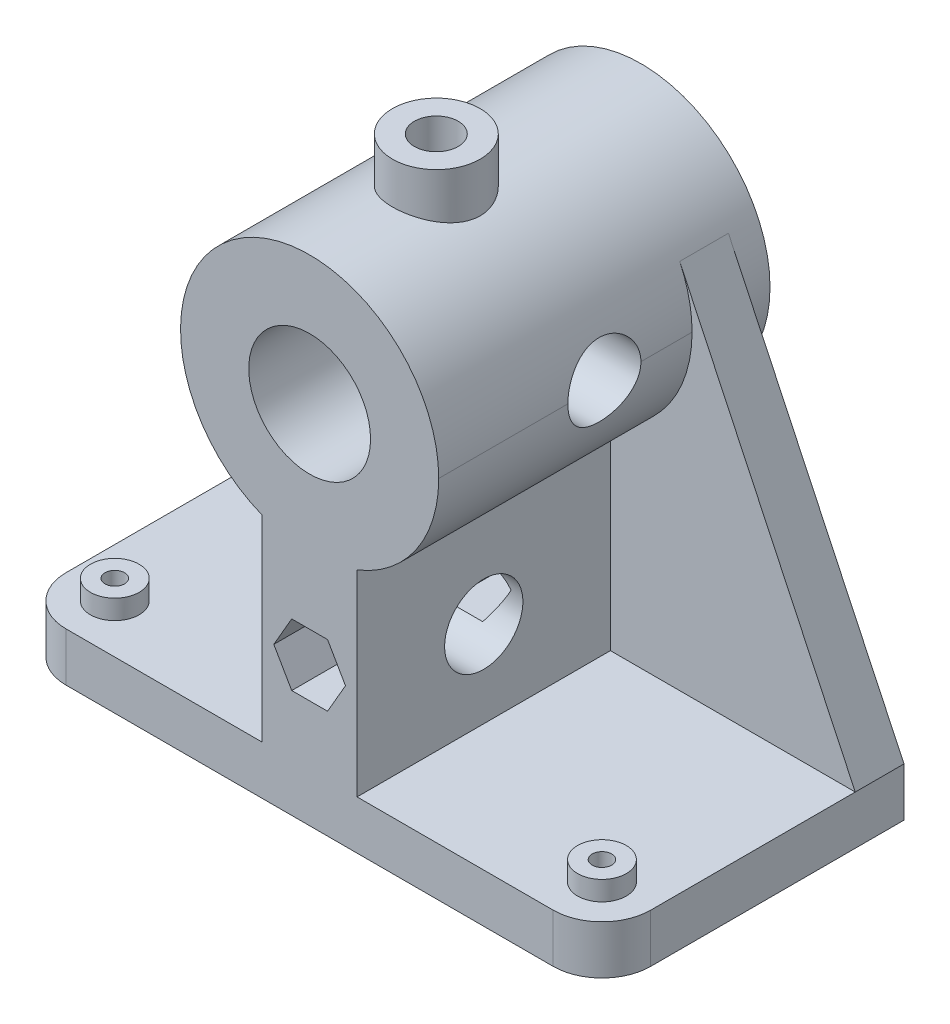
SolidWorks part; units mm, degrees
ref_plane "前视基准面" through (0, 0, 0) normal (0, 0, 1) x (1, 0, 0)
ref_plane "上视基准面" through (0, 0, 0) normal (0, 1, 0) x (1, 0, 0)
ref_plane "右视基准面" through (0, 0, 0) normal (1, 0, 0) x (0, 0, -1)
other "Configuration Table"
sketch "草图1" plane through (0, 0, 0) normal (0, 1, 0) x (1, 0, 0)
  line L1 (-60, 26) -> (60, 26)
  line L2 (-60, 26) -> (-60, -16)
  line L3 (-50, -26) -> (50, -26)
  line L4 (60, 26) -> (60, -16)
  line L5 (-60, 26) -> (60, -26) construction
  line L6 (-60, -26) -> (60, 26) construction
  arc A0 (60, -16) -> (50, -26) centre (50, -16) cw
  arc A1 (-50, -26) -> (-60, -16) centre (-50, -16) cw
  point P0 (0, 0)
  dimension "D1" = 10
  dimension "D3" = 52
  dimension "D2" = 120
extrude "凸台-拉伸1" add sketch "草图1" along normal blind 10
sketch "草图2" plane through (0, 0, 0) normal (0, 0, 1) x (1, 0, 0)
  circle A0 centre (0, 75) radius 26.5
  dimension "D2" = 53
  dimension "D1" = 75
extrude "凸台-拉伸2" add sketch "草图2" along normal blind 26 and the other way blind 42 separate body
sketch "草图3" plane through (0, 0, 26) normal (0, 0, 1) x (1, 0, 0)
  circle A0 centre (0, 75) radius 12.5
  dimension "D1" = 25
extrude "切除-拉伸1" cut sketch "草图3" against normal through all
sketch "草图4" plane through (0, 0, -26) normal (0, 0, -1) x (-1, 0, 0)
  line L0 (-60, 10) -> (-23.9627, 86.3155)
  line L1 (60, 10) -> (23.9627, 86.3155)
  line L2 (-60, 10) -> (-60, 0)
  line L3 (-60, 0) -> (60, 0)
  line L4 (-60, 0) -> (60, 0) construction
  line L5 (60, 0) -> (60, 10)
  circle A0 centre (0, 75) radius 26.5 construction
  arc A1 (-23.9627, 86.3155) -> (23.9627, 86.3155) centre (0, 75) ccw
extrude "凸台-拉伸3" add sketch "草图4" along normal blind 10
sketch "草图5" plane through (0, 0, 0) normal (1, 0, 0) x (0, 0, -1)
  circle A0 centre (8, 75) radius 7.5
  dimension "D1" = 15
extrude "切除-拉伸2" cut sketch "草图5" against normal through all both and the other way through all
sketch "草图6" plane through (0, 10, 0) normal (0, 1, 0) x (1, 0, 0)
  line L0 (-26.5, -26) -> (26.5, -26) construction
  line L1 (-9.7345, 26) -> (9.7345, 26)
  line L2 (-9.7345, 26) -> (-9.7345, -26)
  line L3 (-9.7345, -26) -> (9.7345, -26)
  line L4 (9.7345, 26) -> (9.7345, -26)
  line L5 (-9.7345, 26) -> (9.7345, -26) construction
  line L6 (-9.7345, -26) -> (9.7345, 26) construction
  point P0 (0, 0)
extrude "凸台-拉伸4" add sketch "草图6" along normal up to surface (40.3527 mm away)
ref_plane "基准面1" through (0, 110, 0) normal (0, 1, 0) x (1, 0, 0)
sketch "草图7" plane through (0, 110, 0) normal (0, 1, 0) x (1, 0, 0)
  circle A0 centre (0, 0) radius 9
  dimension "D1" = 18
extrude "凸台-拉伸5" add sketch "草图7" against normal up to next
sketch "草图8" plane through (0, 110, 0) normal (0, 1, 0) x (1, 0, 0)
  circle A0 centre (0, 0) radius 4.5
  dimension "D1" = 9
extrude "切除-拉伸3" cut sketch "草图8" against normal up to surface (22.5 mm away)
sketch "草图9" plane through (0, 10, 0) normal (0, 1, 0) x (1, 0, 0)
  circle A0 centre (-50, -16) radius 5
  circle A1 centre (50, -16) radius 5
  dimension "D1" = 10
  dimension "D2" = 10
extrude "凸台-拉伸6" add sketch "草图9" along normal blind 4
sketch "草图10" plane through (0, 14, 0) normal (0, 1, 0) x (1, 0, 0)
  circle A0 centre (-50, -16) radius 2
  circle A1 centre (50, -16) radius 2
  dimension "D1" = 4
  dimension "D2" = 4
extrude "切除-拉伸4" cut sketch "草图10" against normal up to surface (14 mm away) up to face at (0, 0, 2.6904)
sketch "草图11" plane through (-9.7345, 0, 0) normal (-1, 0, 0) x (0, 0, 1)
  circle A0 centre (0, 27.7112) radius 8.0339
extrude "切除-拉伸5" cut sketch "草图11" against normal up to surface (19.4691 mm away) up to face at (9.7345, 30.1764, 0)
sketch "草图12" plane through (0, 0, 26) normal (0, 0, 1) x (1, 0, 0)
  line L1 (7.3555, 28.5732) -> (3.6777, 34.9432)
  line L2 (3.6777, 34.9432) -> (-3.6777, 34.9432)
  line L3 (-3.6777, 34.9432) -> (-7.3555, 28.5732)
  line L4 (-7.3555, 28.5732) -> (-3.6777, 22.2031)
  line L5 (-3.6777, 22.2031) -> (3.6777, 22.2031)
  line L6 (3.6777, 22.2031) -> (7.3555, 28.5732)
  circle A0 centre (0, 28.5732) radius 6.37 construction
extrude "切除-拉伸6" cut sketch "草图12" against normal up to surface (62 mm away) up to face at (0, 25.8026, -36)
